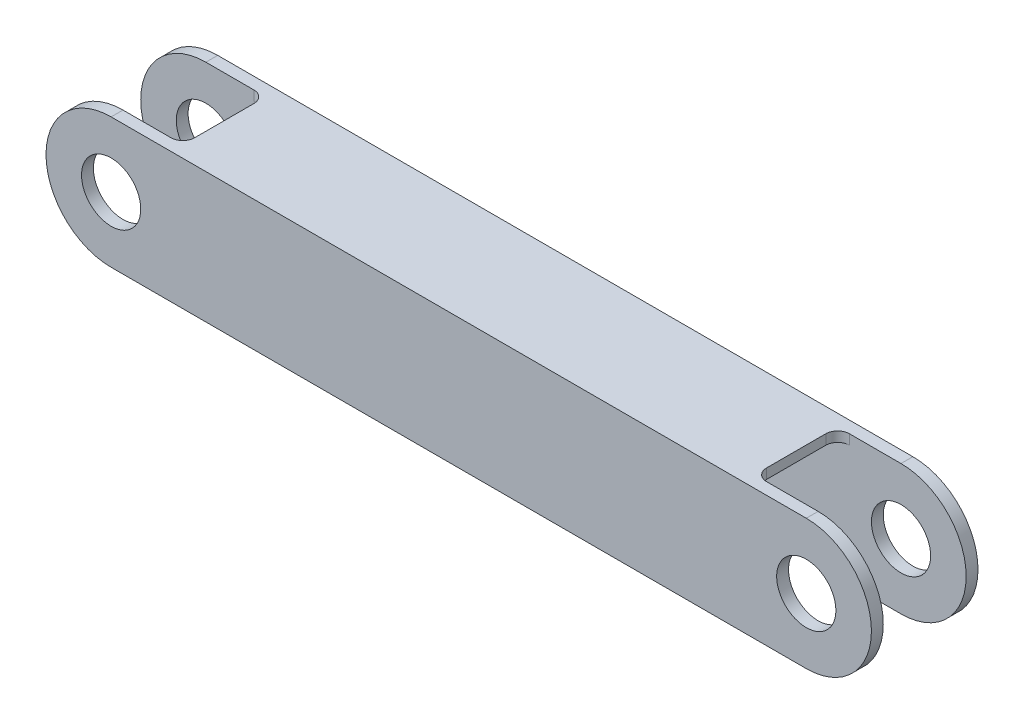
SolidWorks part; units mm, degrees
material "AISI 1045 Steel, cold drawn"
ref_plane "Front Plane" through (0, 0, 0) normal (0, 0, 1) x (1, 0, 0)
ref_plane "Top Plane" through (0, 0, 0) normal (0, 1, 0) x (1, 0, 0)
ref_plane "Right Plane" through (0, 0, 0) normal (1, 0, 0) x (0, 0, -1)
sketch "Sketch1" plane through (0, 0, 0) normal (0, 0, 1) x (1, 0, 0)
  line L0 (0, 0) -> (0, 22) construction
  line L1 (-58.7, 0) -> (58.7, 0)
  line L3 (-58.7, 22) -> (58.7, 22)
  circle A0 centre (-58.7, 11) radius 5
  circle A1 centre (58.7, 11) radius 5
  arc A2 (-58.7, 22) -> (-58.7, 0) centre (-58.7, 11) ccw
  arc A3 (58.7, 0) -> (58.7, 22) centre (58.7, 11) ccw
  point P10 (0, 11)
extrude "Boss-Extrude1" add sketch "Sketch1" along normal blind 2
sketch "Sketch2" plane through (0, 0, 2) normal (0, 0, 1) x (1, 0, 0)
  line L0 (58.7, 22) -> (-58.7, 22) construction
  line L1 (-48.5968, 22) -> (47.9878, 22)
  line L2 (-48.5968, 22) -> (-48.5968, 20.3174)
  line L3 (-48.5968, 20.3174) -> (47.9878, 20.3174)
  line L4 (47.9878, 22) -> (47.9878, 20.3174)
extrude "Boss-Extrude2" add sketch "Sketch2" along normal blind 3.5
mirror "Mirror1" about plane through (0, 0, 5.5) normal (0, 0, 1) of "Boss-Extrude1", "Boss-Extrude2"
mirror "Mirror2" about plane through (0, 0, 9) normal (0, 0, -1) of bodies 103
fillet "Fillet1" radius 2 4 edges at (-48.5968, 21.1587, 16) (47.9878, 21.1587, 16) (47.9878, 21.1587, 2) (-48.5968, 21.1587, 2)
